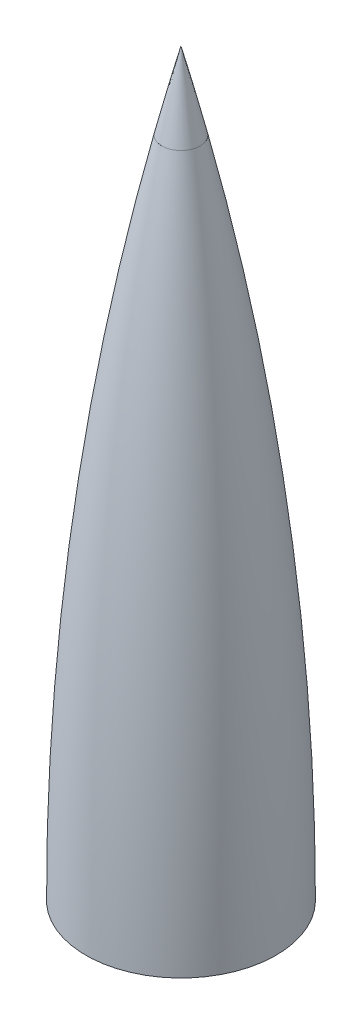
SolidWorks part; units mm, degrees
other "Nose Cone Tip"
other "Nose Cone Body" parameters "D1"=22.7851, "D2"=319.7208, "D3"=268.3185, "D4"=78.359
material "E-Glass Fiber"
ref_plane "Front Plane" through (0, 0, 0) normal (0, 0, 1) x (1, 0, 0)
ref_plane "Top Plane" through (0, 0, 0) normal (0, 1, 0) x (1, 0, 0)
ref_plane "Right Plane" through (0, 0, 0) normal (1, 0, 0) x (0, 0, -1)
sketch "Sketch1" plane through (0, 0, 0) normal (0, 0, 1) x (1, 0, 0)
  line L0 (0, 0) -> (0, 546.1) construction
  line L1 (78.359, 0) -> (78.359, -254) construction
  line L2 (0, 546.1) -> (15.6818, 546.1)
  line L3 (78.359, 0) -> (0, 0)
  line L4 (0, 0) -> (0, 546.1)
  line L5 (0, 546.1) -> (0, 609.6) construction
  line L6 (0, 546.1) -> (0, 609.6) construction
  line L7 (15.6818, 546.1) -> (78.359, 546.1) construction
  arc A0 (78.359, 0) -> (15.6818, 546.1) centre (-2332.0361, 0) ccw
  arc A1 (15.6818, 546.1) -> (0, 609.6) centre (-2332.0361, 0) ccw construction
  dimension "D1" = 609.6
  dimension "D2" = 156.718
  dimension "D3" = 254
  dimension "D4" = 63.5
revolve "Revolve1" add sketch "Sketch1" angle 360 about L4
shell "Shell1" thickness 2.1844
sketch "Sketch2" plane through (0, 0, 0) normal (0, 0, 1) x (1, 0, 0)
  line L0 (0, 546.1) -> (0, 609.6)
  line L1 (13.439, 546.1) -> (-13.439, 546.1) construction
  line L2 (0, 546.1) -> (15.6818, 546.1)
  line L3 (0, 609.6) -> (0, 0) construction
  arc A0 (15.6818, 546.1) -> (0, 609.6) centre (-2332.0476, -0.0029) ccw
  arc A1 (78.359, 0) -> (15.6818, 546.1) centre (-2332.0361, 0) ccw construction
  dimension "D1" = 63.5
revolve "Revolve2" add sketch "Sketch2" angle 360 about L3
equation "\"Length\"= 24"
equation "\"Base Diameter\"= 6.17"
equation "\"Wall thickness\"= 0.086"
equation "\"D1@Sketch1\"=\"Length\""
equation "\"D2@Sketch1\"=\"Base Diameter\""
equation "\"Nose Cone Length\"= 2.5"
equation "\"D4@Sketch1\"=\"Nose Cone Length\""
equation "\"D1@Shell1\"=\"Wall thickness\""
equation "\"D1@Sketch2\"=\"Nose Cone Length\""
